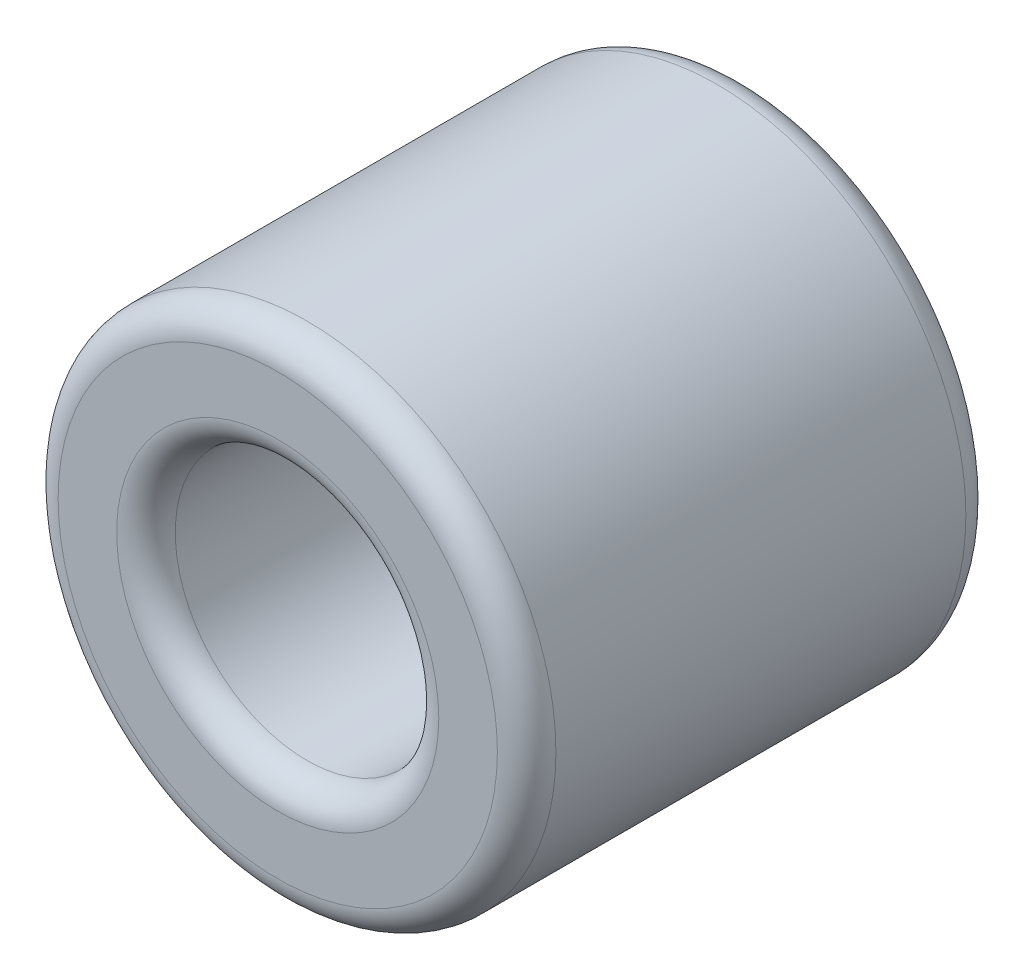
SolidWorks part; units mm, degrees
ref_plane "Front Plane" through (0, 0, 0) normal (0, 0, 1) x (1, 0, 0)
ref_plane "Top Plane" through (0, 0, 0) normal (0, 1, 0) x (1, 0, 0)
ref_plane "Right Plane" through (0, 0, 0) normal (1, 0, 0) x (0, 0, -1)
sketch "Sketch1" plane through (0, 0, 0) normal (0, 0, 1) x (1, 0, 0)
  circle A0 centre (0, 0) radius 2.25
  circle A1 centre (0, 0) radius 4.25
  dimension "D1" = 4.5
  dimension "D2" = 2
extrude "Boss-Extrude1" add sketch "Sketch1" along normal blind 8
fillet "Fillet1" radius 0.5 4 edges at (2.25, 0, 0) (4.25, 0, 0) (2.25, 0, 8) (4.25, 0, 8)
